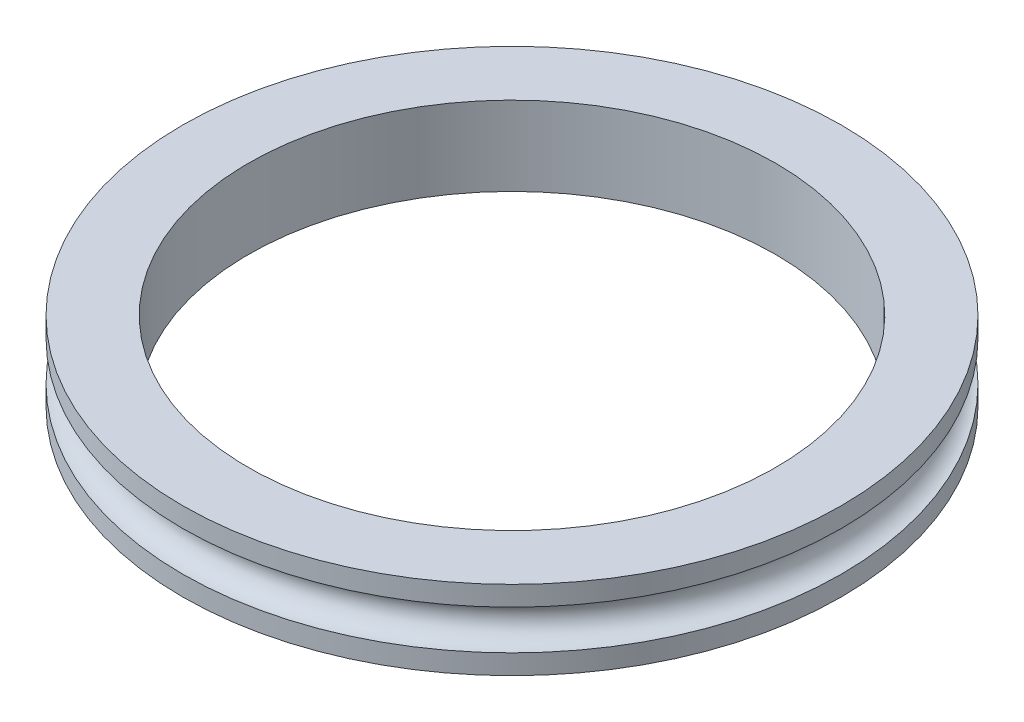
SolidWorks part; units mm, degrees
ref_plane "Alzado" through (0, 0, 0) normal (0, 0, 1) x (1, 0, 0)
ref_plane "Planta" through (0, 0, 0) normal (0, 1, 0) x (1, 0, 0)
ref_plane "Vista lateral" through (0, 0, 0) normal (1, 0, 0) x (0, 0, -1)
sketch "Croquis1" plane through (0, 0, 0) normal (0, 1, 0) x (1, 0, 0)
  circle A0 centre (0, 0) radius 12.5
  dimension "D1" = 25
extrude "Saliente-Extruir1" add sketch "Croquis1" along normal mid plane 3
ref_axis "Eje1" through (0, 1.5, 0) along (0, -1, 0)
sketch "Croquis2" plane through (0, 0, 0) normal (1, 0, 0) x (0, 0, -1)
  line L0 (12.5, -1.5) -> (12.5, 1.5) construction
  circle A0 centre (12.5, 0) radius 0.75
  dimension "D1" = 1.5
revolve "Cortar-Revolución1" cut sketch "Croquis2" angle 360 about axis through (0, 1.5, 0) along (0, -1, 0)
sketch "Croquis4" plane through (0, -1.5, 0) normal (0, -1, 0) x (1, 0, 0)
  circle A0 centre (0, 0) radius 10
  dimension "D1" = 20
extrude "Cortar-Extruir1" cut sketch "Croquis4" against normal through all
